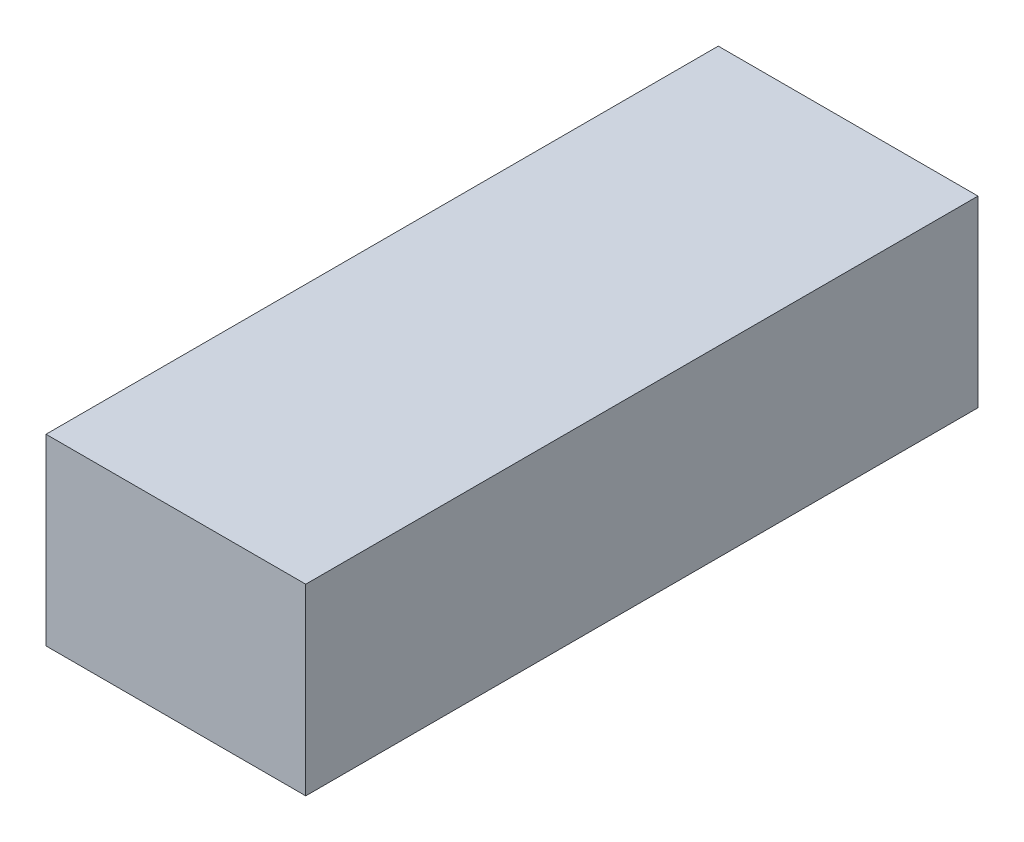
SolidWorks part; units mm, degrees
ref_plane "Ebene vorne" through (0, 0, 0) normal (0, 0, 1) x (1, 0, 0)
ref_plane "Ebene oben" through (0, 0, 0) normal (0, 1, 0) x (1, 0, 0)
ref_plane "Ebene rechts" through (0, 0, 0) normal (1, 0, 0) x (0, 0, -1)
sketch "Sketch1" plane through (0, 0, 0) normal (0, 1, 0) x (1, 0, 0)
  line L1 (0, 0) -> (17, 0)
  line L2 (0, 0) -> (0, 44)
  line L3 (0, 44) -> (17, 44)
  line L4 (17, 0) -> (17, 44)
  dimension "D1" = 44
  dimension "D2" = 17
extrude "Boss-Extrude1" add sketch "Sketch1" along normal blind 12
